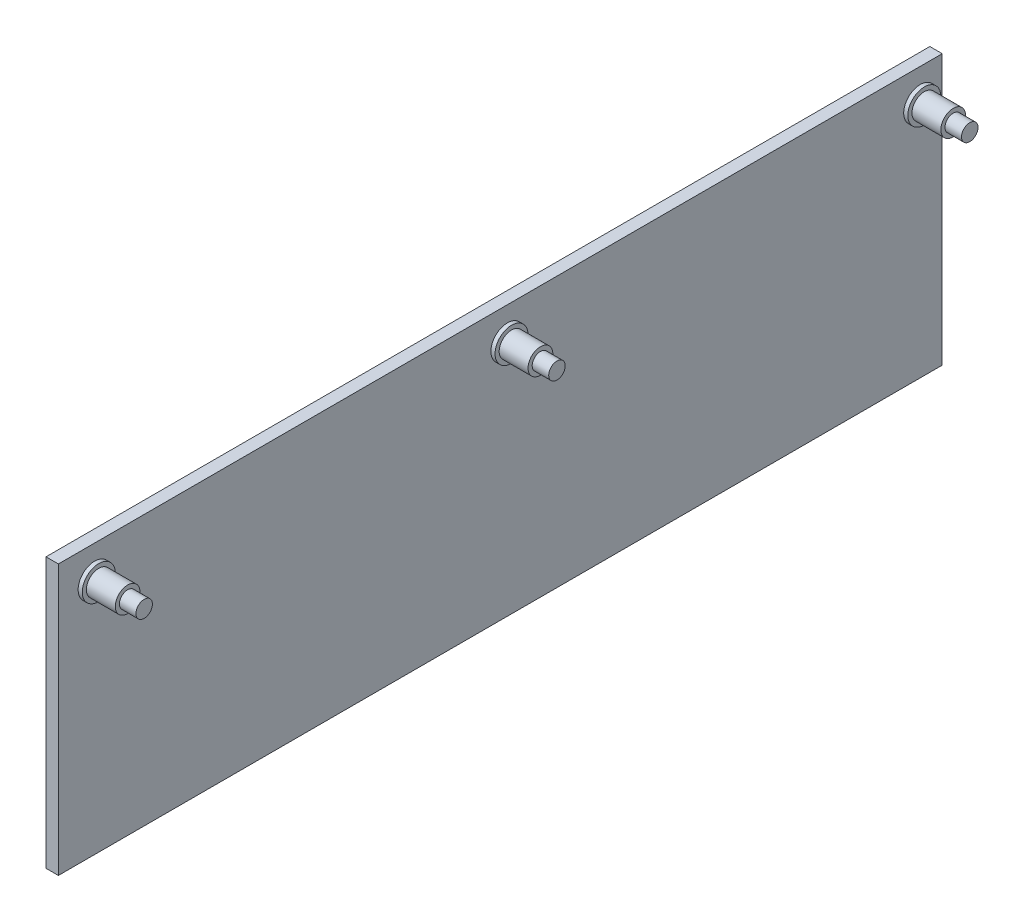
SolidWorks part; units mm, degrees
ref_plane "前视基准面" through (0, 0, 0) normal (0, 0, 1) x (1, 0, 0)
ref_plane "上视基准面" through (0, 0, 0) normal (0, 1, 0) x (1, 0, 0)
ref_plane "右视基准面" through (0, 0, 0) normal (1, 0, 0) x (0, 0, -1)
other "Configuration Table"
sketch "草图1" plane through (0, 0, 0) normal (1, 0, 0) x (0, 0, -1)
  line L0 (0, 0) -> (0, 65.3592)
  line L1 (0, 65.3592) -> (-214.118, 65.3592)
  line L2 (-214.118, 65.3592) -> (-214.118, 0)
  line L3 (-214.118, 0) -> (0, 0)
extrude "凸台-拉伸1" add sketch "草图1" along normal blind 3
sketch "草图2" plane through (3, 0, 0) normal (1, 0, 0) x (0, 0, -1)
  circle A0 centre (-5.3348, 57.5545) radius 2
  dimension "D1" = 4
extrude "凸台-拉伸2" add sketch "草图2" along normal blind 12
sketch "草图3" plane through (3, 0, 0) normal (1, 0, 0) x (0, 0, -1)
  line L0 (-5.3348, 57.5545) -> (-139.9179, 57.5545) construction
  circle A0 centre (-105.3348, 57.5545) radius 2
  dimension "D1" = 4
  dimension "D2" = 100
extrude "凸台-拉伸3" add sketch "草图3" along normal blind 12
sketch "草图4" plane through (3, 0, 0) normal (1, 0, 0) x (0, 0, -1)
  line L0 (-5.3348, 57.5545) -> (-372.8005, 57.5545) construction
  circle A0 centre (-205.3348, 57.5545) radius 2
  dimension "D1" = 4
  dimension "D2" = 200
extrude "凸台-拉伸4" add sketch "草图4" along normal blind 12
sketch "草图5" plane through (3, 0, 0) normal (1, 0, 0) x (0, 0, -1)
  circle A2 centre (-5.3348, 57.5545) radius 3
  circle A3 centre (-5.3348, 57.5545) radius 3
  dimension "D1" = 1
extrude "凸台-拉伸5" add sketch "草图5" along normal blind 8
sketch "草图6" plane through (3, 0, 0) normal (1, 0, 0) x (0, 0, -1)
  circle A2 centre (-5.3348, 57.5545) radius 4
  circle A3 centre (-5.3348, 57.5545) radius 4
  dimension "D1" = 1
extrude "凸台-拉伸6" add sketch "草图6" along normal blind 1
sketch "草图7" plane through (3, 0, 0) normal (1, 0, 0) x (0, 0, -1)
  circle A2 centre (-105.3348, 57.5545) radius 3
  circle A3 centre (-105.3348, 57.5545) radius 3
  dimension "D1" = 1
extrude "凸台-拉伸7" add sketch "草图7" along normal blind 8
sketch "草图8" plane through (3, 0, 0) normal (1, 0, 0) x (0, 0, -1)
  circle A2 centre (-205.3348, 57.5545) radius 3
  circle A3 centre (-205.3348, 57.5545) radius 3
  dimension "D1" = 1
extrude "凸台-拉伸8" add sketch "草图8" along normal blind 8
sketch "草图9" plane through (3, 0, 0) normal (1, 0, 0) x (0, 0, -1)
  circle A2 centre (-105.3348, 57.5545) radius 4
  circle A3 centre (-105.3348, 57.5545) radius 4
  dimension "D1" = 1
extrude "凸台-拉伸9" add sketch "草图9" along normal blind 1
sketch "草图10" plane through (3, 0, 0) normal (1, 0, 0) x (0, 0, -1)
  circle A2 centre (-205.3348, 57.5545) radius 4
  circle A3 centre (-205.3348, 57.5545) radius 4
  dimension "D1" = 1
extrude "凸台-拉伸10" add sketch "草图10" along normal blind 1
